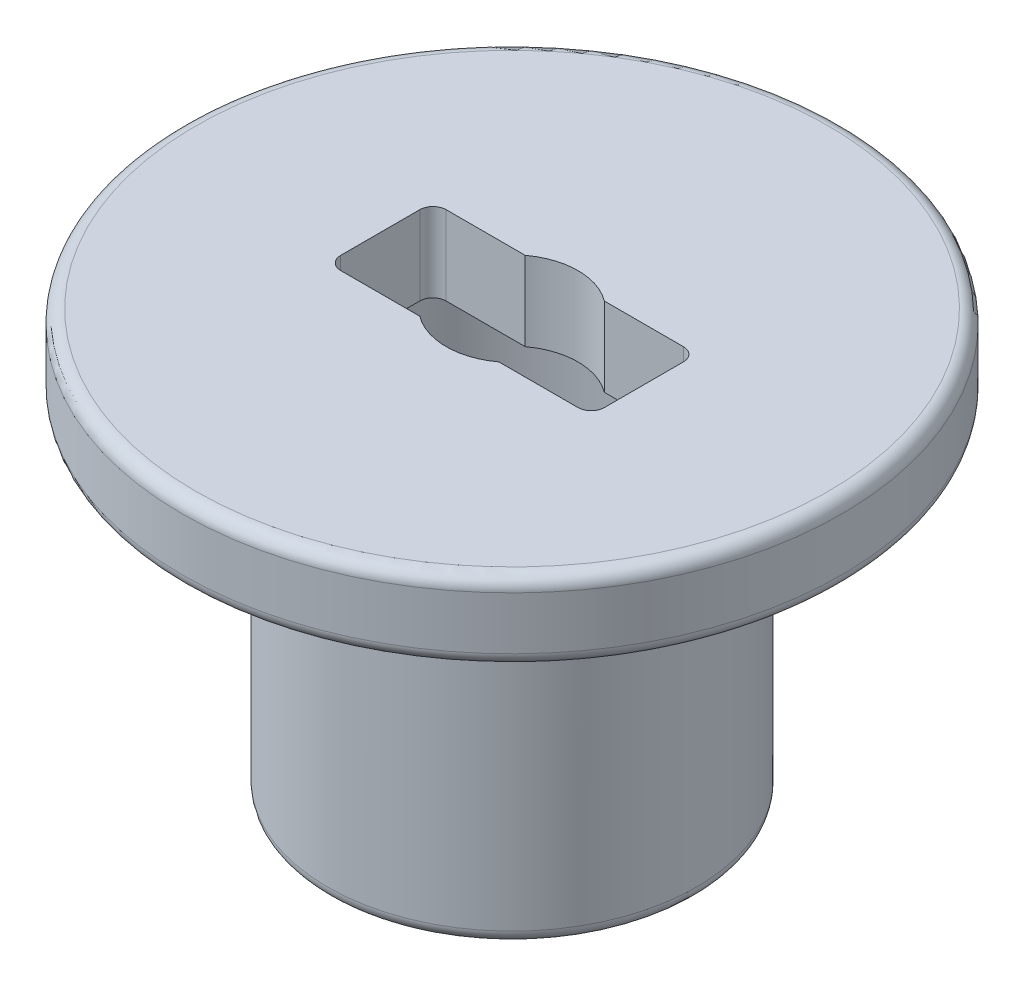
SolidWorks part; units mm, degrees
ref_plane "前视基准面" through (0, 0, 0) normal (0, 0, 1) x (1, 0, 0)
ref_plane "上视基准面" through (0, 0, 0) normal (0, 1, 0) x (1, 0, 0)
ref_plane "右视基准面" through (0, 0, 0) normal (1, 0, 0) x (0, 0, -1)
sketch "Sketch1" plane through (0, 0, 0) normal (0, 1, 0) x (1, 0, 0)
  line L6 (1.5, 2) -> (4.5, 2)
  line L7 (1.5, -2) -> (4.5, -2)
  line L8 (-4.5, 2) -> (-1.5, 2)
  line L9 (-5, 1.5) -> (-5, -1.5)
  line L10 (-4.5, -2) -> (-1.5, -2)
  line L11 (5, 1.5) -> (5, -1.5)
  line L12 (-5, 2) -> (-4.7821, 1.9128) construction
  line L13 (-5, -2) -> (-4.7821, -1.9128) construction
  line L14 (-5, 0) -> (-12.5, 0) construction
  line L16 (4.7821, 1.9128) -> (5, 2) construction
  line L17 (4.7821, -1.9128) -> (5, -2) construction
  circle A0 centre (0, 0) radius 12.5
  arc A5 (-5, -1.5) -> (-4.5, -2) centre (-4.5, -1.5) ccw
  arc A6 (-4.5, 2) -> (-5, 1.5) centre (-4.5, 1.5) ccw
  arc A7 (4.5, -2) -> (5, -1.5) centre (4.5, -1.5) ccw
  arc A8 (4.5, 2) -> (5, 1.5) centre (4.5, 1.5) cw
  arc A9 (-1.5, -2) -> (1.5, -2) centre (0, 0) ccw
  arc A11 (1.5, 2) -> (-1.5, 2) centre (0, 0) ccw
  dimension "D1" = 25
  dimension "D2" = 10
  dimension "D4" = 0.5
  dimension "D3" = 4
extrude "Boss-Extrude1" add sketch "Sketch1" along normal blind 3
sketch "Sketch3" plane through (0, 0, 0) normal (0, -1, 0) x (1, 0, 0)
  line L0 (0, 0) -> (-12.5, 0) construction
  circle A0 centre (0, 0) radius 12.5 construction
  circle A1 centre (-10.5, 0) radius 1
  dimension "D1" = 10.5
extrude "Boss-Extrude2" add sketch "Sketch3" along normal blind 3
sketch "Sketch4" plane through (0, 0, 0) normal (0, -1, 0) x (1, 0, 0)
  circle A0 centre (0, 0) radius 7
  dimension "D1" = 14
extrude "Boss-Extrude3" add sketch "Sketch4" along normal blind 13
sketch "Sketch5" plane through (0, 0, 0) normal (0, 1, 0) x (1, 0, 0)
  circle A0 centre (0, 0) radius 6
  dimension "D1" = 12
extrude "Cut-Extrude1" cut sketch "Sketch5" against normal up to next
fillet "Fillet2" radius 0.5 2 edges at (0, 0, 12.5) (0, 3, 12.5)
fillet "Fillet3" radius 0.5 1 edges at (0, -13, -7)
